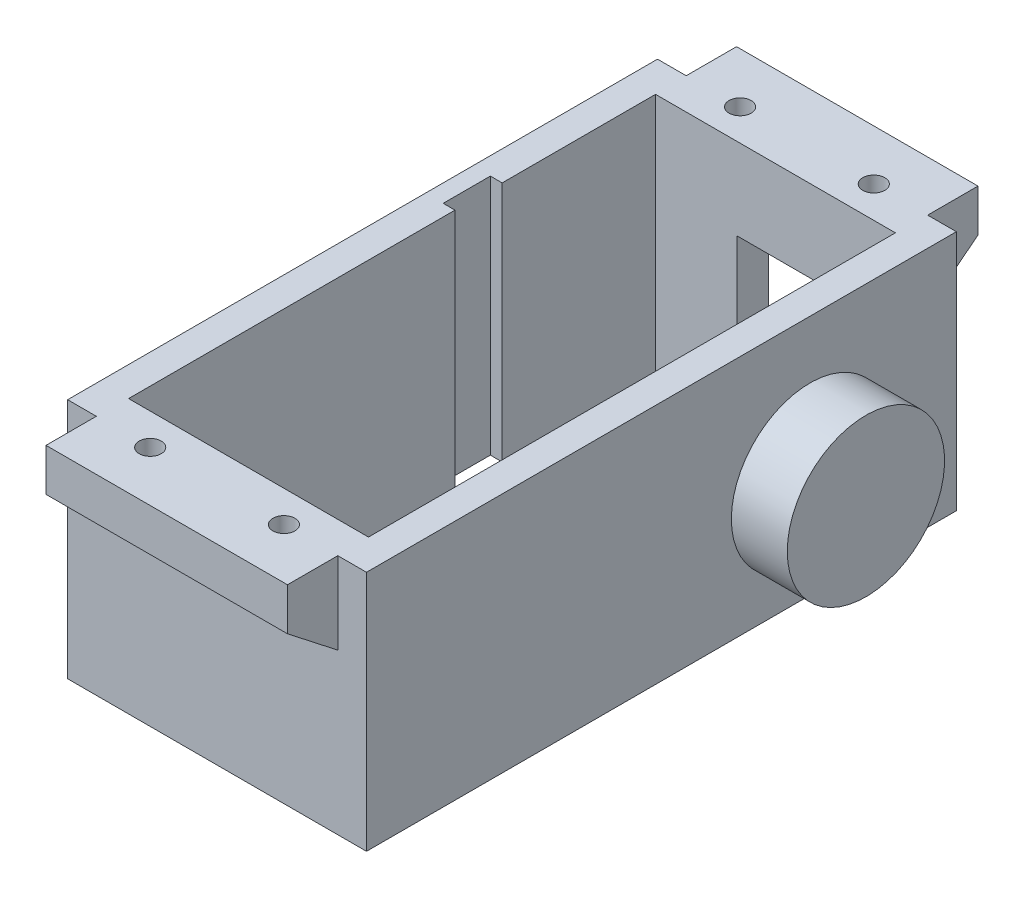
SolidWorks part; units mm, degrees
ref_plane "前视基准面" through (0, 0, 0) normal (0, 0, 1) x (1, 0, 0)
ref_plane "上视基准面" through (0, 0, 0) normal (0, 1, 0) x (1, 0, 0)
ref_plane "右视基准面" through (0, 0, 0) normal (1, 0, 0) x (0, 0, -1)
other "Configuration Table"
sketch "草图1" plane through (0, 0, 0) normal (0, 1, 0) x (1, 0, 0)
  line L1 (19, -37.5) -> (-19, -37.5)
  line L2 (19, -37.5) -> (19, 37.5)
  line L3 (19, 37.5) -> (-19, 37.5)
  line L4 (-19, -37.5) -> (-19, 37.5)
  line L5 (19, -37.5) -> (-19, 37.5) construction
  line L6 (19, 37.5) -> (-19, -37.5) construction
  point P0 (0, 0)
  dimension "D1" = 75
  dimension "D2" = 38
extrude "凸台-拉伸1" add sketch "草图1" along normal blind 30.73
sketch "草图2" plane through (-19, 0, 0) normal (-1, 0, 0) x (0, 0, 1)
  line L2 (-37.5, 30.73) -> (-37.5, 0) construction
  line L4 (-37.5, 0) -> (37.5, 0) construction
  circle A0 centre (-18.89, 13.38) radius 10
  point P2 (-18.89, 23.38)
  point P3 (-18.89, 3.38)
  point P4 (-28.89, 13.38)
  point P5 (-8.89, 13.38)
  dimension "D2" = 20
  dimension "D1" = 18.61
  dimension "D3" = 13.38
extrude "凸台-拉伸2" add sketch "草图2" along normal blind 7.11
sketch "草图3" plane through (0, 0, -37.5) normal (0, 0, -1) x (-1, 0, 0)
  line L0 (-19, 30.73) -> (19, 30.73) construction
  line L1 (15.35, 20.33) -> (-15.35, 20.33)
  line L2 (15.35, 20.33) -> (15.35, 30.73)
  line L3 (15.35, 30.73) -> (-15.35, 30.73)
  line L4 (-15.35, 20.33) -> (-15.35, 30.73)
  line L5 (15.35, 20.33) -> (-15.35, 30.73) construction
  line L6 (15.35, 30.73) -> (-15.35, 20.33) construction
  point P0 (0, 25.53)
  dimension "D1" = 30.7
  dimension "D2" = 10.4
extrude "凸台-拉伸3" add sketch "草图3" along normal blind 6.4
sketch "草图5" plane through (0, 30.73, 0) normal (0, 1, 0) x (1, 0, 0)
  line L1 (15.25, -33.5) -> (-15.25, -33.5)
  line L2 (15.25, -33.5) -> (15.25, 33.5)
  line L3 (15.25, 33.5) -> (-15.25, 33.5)
  line L4 (-15.25, -33.5) -> (-15.25, 33.5)
  line L5 (15.25, -33.5) -> (-15.25, 33.5) construction
  line L6 (15.25, 33.5) -> (-15.25, -33.5) construction
  point P0 (0, 0)
  dimension "D1" = 67
  dimension "D2" = 30.5
extrude "切除-拉伸1" cut sketch "草图5" against normal through all
mirror "镜向2" about plane through (0, 0, 0) normal (1, 0, 0) of "凸台-拉伸2"
sketch "草图6" plane through (0, 0, -37.5) normal (0, 0, -1) x (-1, 0, 0)
  line L0 (-19, 0) -> (19, 0) construction
  line L1 (4.9, 0) -> (-4.9, 0)
  line L2 (4.9, 0) -> (4.9, 20.33)
  line L3 (4.9, 20.33) -> (-4.9, 20.33)
  line L4 (-4.9, 0) -> (-4.9, 20.33)
  line L5 (4.9, 0) -> (-4.9, 20.33) construction
  line L6 (4.9, 20.33) -> (-4.9, 0) construction
  line L7 (-15.35, 20.33) -> (15.35, 20.33) construction
  point P0 (0, 10.165)
  dimension "D1" = 9.8
extrude "切除-拉伸2" cut sketch "草图6" against normal up to next
sketch "草图7" plane through (15.35, 0, 0) normal (1, 0, 0) x (0, 0, -1)
  line L0 (37.5, 20.33) -> (43.9, 25.3302)
  line L1 (43.9, 30.73) -> (43.9, 20.33) construction
  line L2 (43.9, 25.3302) -> (43.9, 20.33)
  line L3 (43.9, 20.33) -> (37.5, 20.33) construction
  line L4 (43.9, 20.33) -> (37.5, 20.33)
  line L5 (37.5, 30.73) -> (37.5, 0) construction
  dimension "D1" = 128
extrude "切除-拉伸3" cut sketch "草图7" against normal up to next
mirror "镜向4" about plane through (0, 0, 0) normal (0, 0, 1) of "切除-拉伸3", "凸台-拉伸3"
sketch "草图8" plane through (0, 30.73, 0) normal (0, 1, 0) x (1, 0, 0)
  line L0 (-15.35, 37.5) -> (15.35, 37.5) construction
  line L1 (19, 37.5) -> (15.35, 37.5) construction
  line L2 (0, 37.5) -> (0, 43.9) construction
  line L3 (-15.35, 43.9) -> (15.35, 43.9) construction
  line L4 (-19, 0) -> (19, 0) construction
  line L5 (-19, 37.5) -> (-19, -37.5) construction
  line L6 (19, -37.5) -> (19, 37.5) construction
  circle A0 centre (-8.5, 37.5) radius 1.4
  circle A1 centre (8.5, 37.5) radius 1.4
  circle A2 centre (8.5, -37.5) radius 1.4
  circle A3 centre (-8.5, -37.5) radius 1.4
  dimension "D3" = 2.8
  dimension "D1" = 17
  dimension "D2" = 75
extrude "切除-拉伸4" cut sketch "草图8" against normal blind 7.4
sketch "草图10" plane through (-15.25, 0, 0) normal (1, 0, 0) x (0, 0, -1)
  line L0 (33.5, 30.73) -> (-33.5, 30.73) construction
  line L1 (14, 0) -> (8, 0)
  line L2 (14, 0) -> (14, 30.73)
  line L3 (14, 30.73) -> (8, 30.73)
  line L4 (8, 0) -> (8, 30.73)
  line L5 (14, 0) -> (8, 30.73) construction
  line L6 (14, 30.73) -> (8, 0) construction
  line L7 (33.5, 0) -> (-33.5, 0) construction
  line L8 (33.5, 0) -> (33.5, 30.73) construction
  point P0 (11, 15.365)
  dimension "D1" = 6
  dimension "D2" = 19.5
extrude "切除-拉伸5" cut sketch "草图10" against normal blind 1.5
